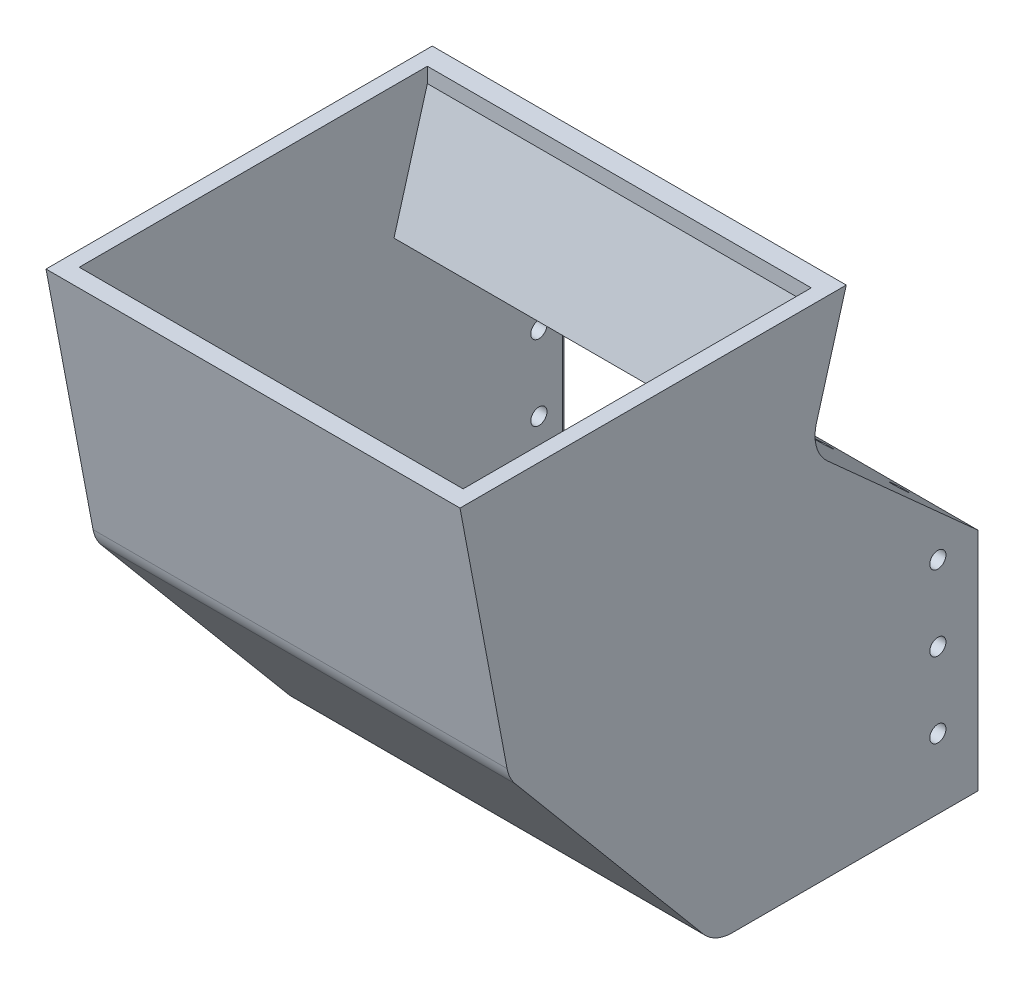
SolidWorks part; units mm, degrees
ref_plane "Front Plane" through (0, 0, 0) normal (0, 0, 1) x (1, 0, 0)
ref_plane "Top Plane" through (0, 0, 0) normal (0, 1, 0) x (1, 0, 0)
ref_plane "Right Plane" through (0, 0, 0) normal (1, 0, 0) x (0, 0, -1)
sketch "Sketch3" plane through (0, 0, 0) normal (1, 0, 0) x (0, 0, -1)
  line L3 (-12.9887, 68.7844) -> (89.6369, 68.7844)
  line L6 (124.6369, -5.1138) -> (80, 34.9804)
  line L8 (0, 0) -> (54.6369, -65.1138)
  line L9 (54.6369, -65.1138) -> (124.6369, -65.1138)
  line L10 (124.6369, -65.1138) -> (124.6369, -5.1138)
  line L11 (-12.9887, 68.7844) -> (0, 0)
  line L12 (80, 34.9804) -> (89.6369, 68.7844)
  dimension "D1" = 60
  dimension "D2" = 70
  dimension "D3" = 85
  dimension "D4" = 60
  dimension "D5" = 65.1138
  dimension "D6" = 70
extrude "Boss-Extrude2" add sketch "Sketch3" along normal blind 110
ref_plane "Plane2" through (4, 0, 0) normal (-1, 0, 0) x (0, 0, 1)
sketch "Sketch5" plane through (4, 0, 0) normal (-1, 0, 0) x (0, 0, 1)
  line L10 (-84.3372, 64.7844) -> (-84.3372, 68.7844)
  line L11 (-89.6369, 68.7844) -> (12.9887, 68.7844) construction
  line L13 (8.1626, 64.7844) -> (-84.3372, 64.7844)
  line L15 (-75.4683, 33.6742) -> (-120.6369, -6.8976)
  line L24 (-84.3372, 68.7844) -> (8.1626, 68.7844)
  line L25 (8.1626, 68.7844) -> (8.1626, 64.7844)
  line L30 (-75.4683, 33.6742) -> (-124.6369, -10.4905)
  line L31 (-124.6369, -5.1138) -> (-80, 34.9804) construction
  line L33 (-124.6369, -65.1138) -> (-124.6369, -5.1138) construction
  line L34 (-120.6369, -61.1138) -> (-124.6369, -61.1138)
  line L35 (-124.6369, -61.1138) -> (-124.6369, -10.4905)
  line L38 (-56.5022, -61.1138) -> (-3.7365, 1.7699)
  line L39 (-56.5022, -61.1138) -> (-3.7365, 1.7699)
  line L40 (-120.6369, -6.8976) -> (-120.6369, -61.1138)
  line L42 (-120.6369, -61.1138) -> (-56.5022, -61.1138)
  line L43 (-120.6369, -61.1138) -> (-56.5022, -61.1138)
  line L49 (-3.7365, 1.7699) -> (8.1626, 64.7844)
  line L50 (-3.7365, 1.7699) -> (8.1626, 64.7844)
  line L51 (-84.3372, 64.7844) -> (-75.4683, 33.6742)
  line L52 (-84.3372, 64.7844) -> (-75.4683, 33.6742)
  dimension "D2" = 0
  dimension "D1" = 4
extrude "Cut-Extrude1" cut sketch "Sketch5" against normal blind 102
sketch "Sketch8" plane through (0, -65.1138, 0) normal (0, -1, 0) x (1, 0, 0)
  line L0 (0, -124.6369) -> (110, -124.6369)
  arc A0 (0, -124.6369) -> (110, -124.6369) centre (55, -171.102) cw
  dimension "D1" = 72
extrude "Cut-Extrude2" cut sketch "Sketch8" against normal up to vertex (4 mm away)
fillet "Fillet1" radius 10 3 edges at (55, -65.1138, -54.6369) (55, 34.9804, -80) (55, 0, 0)
sketch "Sketch9" plane through (0, -65.1138, 0) normal (0, -1, 0) x (1, 0, 0)
  circle A0 centre (55, -171.102) radius 79.5 construction
  circle A1 centre (55, -91.602) radius 2.15
  arc A2 (115.7292, -119.7968) -> (-5.7292, -119.7968) centre (55, -171.102) ccw
  arc A3 (115.7292, -119.7968) -> (-5.7292, -119.7968) centre (55, -171.102) ccw construction
  circle A4 centre (77.3977, -94.8223) radius 2.15
  circle A5 centre (97.9809, -104.2223) radius 2.15
  circle A6 centre (115.0821, -119.0406) radius 2.15 construction
  circle A7 centre (127.3157, -138.0765) radius 2.15 construction
  circle A8 centre (133.6908, -159.788) radius 2.15 construction
  circle A9 centre (133.6908, -182.416) radius 2.15 construction
  circle A10 centre (127.3157, -204.1275) radius 2.15 construction
  circle A11 centre (115.0821, -223.1634) radius 2.15 construction
  circle A12 centre (97.9809, -237.9816) radius 2.15 construction
  circle A13 centre (77.3977, -247.3817) radius 2.15 construction
  circle A14 centre (55, -250.602) radius 2.15 construction
  circle A15 centre (32.6023, -247.3817) radius 2.15 construction
  circle A16 centre (12.0191, -237.9816) radius 2.15 construction
  circle A17 centre (-5.0821, -223.1634) radius 2.15 construction
  circle A18 centre (-17.3157, -204.1275) radius 2.15 construction
  circle A19 centre (-23.6908, -182.416) radius 2.15 construction
  circle A20 centre (-23.6908, -159.788) radius 2.15
  circle A21 centre (-17.3157, -138.0765) radius 2.15
  circle A22 centre (-5.0821, -119.0406) radius 2.15
  circle A23 centre (12.0191, -104.2223) radius 2.15
  circle A24 centre (32.6023, -94.8223) radius 2.15
  point P45 (55, -171.102)
  dimension "D2" = 4.3
  dimension "D1" = 7.5
  dimension "D3" = 22
extrude "Cut-Extrude3" cut sketch "Sketch9" against normal up to surface (4 mm away) up to face at (55, -61.1138, -83.0963)
sketch "Sketch10" plane through (0, 59.131, -53.1131) normal (0, 0.7439, -0.6682) x (1, 0, 0)
  line L0 (0, 88.1408) -> (110, 88.1408) construction
  line L1 (0, 96.1408) -> (0, 42.3871) construction
  line L2 (110, 96.1408) -> (110, 42.3871) construction
  line L3 (110, 96.1408) -> (0, 96.1408) construction
  circle A0 centre (55, 88.1408) radius 2.15
  circle A1 centre (75, 88.1408) radius 2.15
  circle A2 centre (95, 88.1408) radius 2.15
  circle A3 centre (35, 88.1408) radius 2.15
  circle A4 centre (15, 88.1408) radius 2.15
  dimension "D2" = 4.3
  dimension "D1" = 8
  dimension "D3" = 3
  dimension "D4" = 3
extrude "Cut-Extrude4" cut sketch "Sketch10" against normal up to surface (4 mm away) up to face at (55, 7.3302, -104.7971)
chamfer "Chamfer1" distance 2.6 angle 45 5 edges at (12.0191, -61.1138, -106.3723) (32.6023, -61.1138, -96.9723) (55, -61.1138, -93.752) (77.3977, -61.1138, -96.9723) (97.9809, -61.1138, -106.3723)
sketch "Sketch12" plane through (110, 0, 0) normal (1, 0, 0) x (0, 0, -1)
  line L0 (120.2788, -6.5758) -> (120.2788, -61.1138) construction
  line L1 (120.2788, -6.5758) -> (120.2788, -61.1138)
  circle A0 centre (113.969, -6.5758) radius 2.15
  circle A1 centre (113.969, -26.5758) radius 2.15
  circle A2 centre (113.969, -46.5758) radius 2.15
  dimension "D1" = 4.3
  dimension "D2" = 3
extrude "Cut-Extrude5" cut sketch "Sketch12" against normal through all contours A1 | A0 | A2
